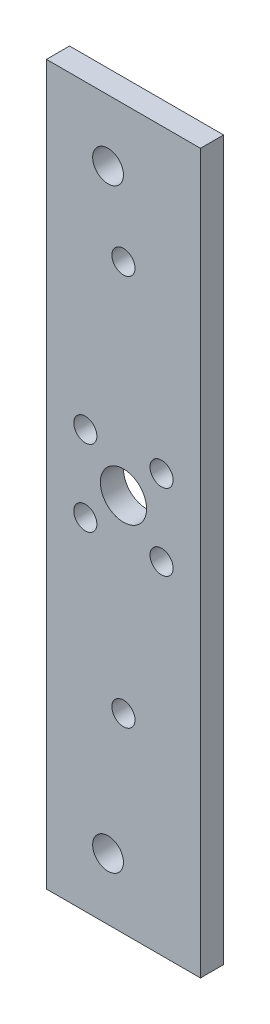
SolidWorks part; units mm, degrees
ref_plane "前视基准面" through (0, 0, 0) normal (0, 0, 1) x (1, 0, 0)
ref_plane "上视基准面" through (0, 0, 0) normal (0, 1, 0) x (1, 0, 0)
ref_plane "右视基准面" through (0, 0, 0) normal (1, 0, 0) x (0, 0, -1)
other "Configuration Table"
sketch "草图1" plane through (0, 0, 0) normal (0, 0, 1) x (1, 0, 0)
  line L1 (85.4719, -52.7604) -> (-85.4719, -52.7604)
  line L2 (85.4719, -52.7604) -> (85.4719, 52.7604)
  line L3 (85.4719, 52.7604) -> (-85.4719, 52.7604)
  line L4 (-85.4719, -52.7604) -> (-85.4719, 52.7604)
  line L5 (85.4719, -52.7604) -> (-85.4719, 52.7604) construction
  line L6 (85.4719, 52.7604) -> (-85.4719, -52.7604) construction
  point P0 (0, 0)
extrude "凸台-拉伸1" add sketch "草图1" along normal blind 3
sketch "草图2" plane through (0, 0, 0) normal (0, 0, -1) x (-1, 0, 0)
  circle A0 centre (7.0546, 18.6609) radius 1.5
  circle A1 centre (16.954, 18.6609) radius 1.5
  circle A2 centre (16.954, 8.7614) radius 1.5
  circle A3 centre (7.0546, 8.7614) radius 1.5
  circle A4 centre (12.0043, 13.7111) radius 3
sketch "草图3" plane through (0, 0, 3) normal (0, 0, 1) x (1, 0, 0)
  line L0 (-22.0043, -47.1889) -> (-22.0043, 72.8111) construction
  line L1 (-2.0043, -30.5389) -> (-22.0043, -30.5389)
  line L2 (-2.0043, -30.5389) -> (-2.0043, 57.9611)
  line L3 (-2.0043, 57.9611) -> (-22.0043, 57.9611)
  line L4 (-22.0043, -30.5389) -> (-22.0043, 57.9611)
  line L5 (-2.0043, -30.5389) -> (-22.0043, 57.9611) construction
  line L6 (-2.0043, 57.9611) -> (-22.0043, -30.5389) construction
  point P0 (-12.0043, 13.7111)
extrude "切除-拉伸1" cut sketch "草图3" against normal through all flip side to cut contours L2 L3 L4 L1
extrude "切除-拉伸2" cut sketch "草图2" against normal through all
sketch "草图4" plane through (0, 0, 0) normal (0, 0, -1) x (-1, 0, 0)
  circle A0 centre (12.0043, 40.0074) radius 1.5
  circle A1 centre (12.0043, -10.7852) radius 1.5
extrude "切除-拉伸3" cut sketch "草图4" against normal through all
sketch "草图9" plane through (0, 52.7604, 0) normal (0, 1, 0) x (1, 0, 0)
  line L4 (-2.0043, 0) -> (-22.0043, 0)
  line L5 (-22.0043, 0) -> (-22.0043, -3)
  line L6 (-22.0043, -3) -> (-2.0043, -3)
  line L7 (-2.0043, -3) -> (-2.0043, 0)
  line L8 (-2.0043, 0) -> (-22.0043, 0)
  line L9 (-22.0043, 0) -> (-22.0043, -3)
  line L10 (-22.0043, -3) -> (-2.0043, -3)
  line L11 (-2.0043, -3) -> (-2.0043, 0)
  dimension "D1" = 0
extrude "凸台-拉伸3" add sketch "草图9" along normal blind 5
sketch "草图10" plane through (0, -30.5389, 0) normal (0, -1, 0) x (1, 0, 0)
  line L4 (-2.0043, 3) -> (-22.0043, 3)
  line L5 (-22.0043, 3) -> (-22.0043, 0)
  line L6 (-22.0043, 0) -> (-2.0043, 0)
  line L7 (-2.0043, 0) -> (-2.0043, 3)
  line L8 (-2.0043, 3) -> (-22.0043, 3)
  line L9 (-22.0043, 3) -> (-22.0043, 0)
  line L10 (-22.0043, 0) -> (-2.0043, 0)
  line L11 (-2.0043, 0) -> (-2.0043, 3)
  dimension "D1" = 0
extrude "凸台-拉伸4" add sketch "草图10" along normal blind 5
sketch "草图11" plane through (0, 0, 3) normal (0, 0, 1) x (1, 0, 0)
  circle A0 centre (-14.0043, 49.7604) radius 2
  circle A1 centre (-14.0043, -27.5389) radius 2
extrude "切除-拉伸4" cut sketch "草图11" against normal blind 5 contours A0 | A1
